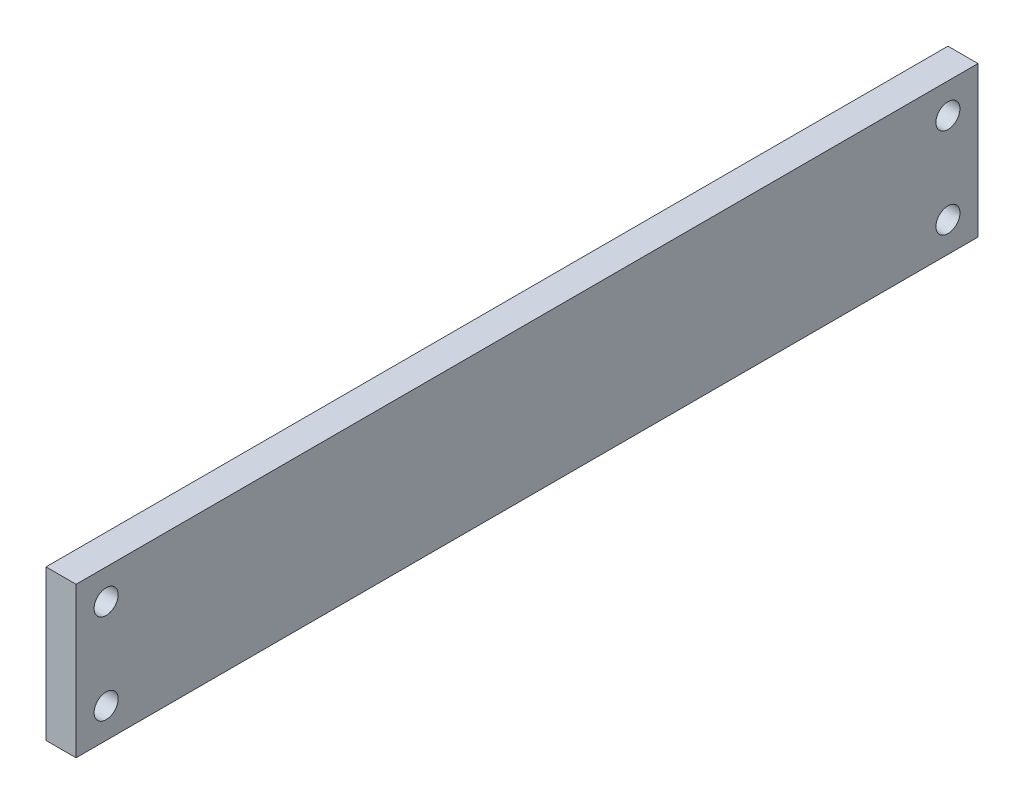
SolidWorks part; units mm, degrees
ref_plane "Front" through (0, 0, 0) normal (0, 0, 1) x (1, 0, 0)
ref_plane "Top" through (0, 0, 0) normal (0, 1, 0) x (1, 0, 0)
ref_plane "Right" through (0, 0, 0) normal (1, 0, 0) x (0, 0, -1)
sketch "Sketch1" plane through (0, 0, 0) normal (1, 0, 0) x (0, 0, -1)
  line L0 (-75, 12.5) -> (75, -12.5) construction
  line L1 (75, -12.5) -> (-75, -12.5)
  line L2 (75, -12.5) -> (75, 12.5)
  line L3 (75, 12.5) -> (-75, 12.5)
  line L4 (-75, -12.5) -> (-75, 12.5)
  dimension "D1" = 25
  dimension "D2" = 150
extrude "Boss-Extrude1" add sketch "Sketch1" along normal blind 5
sketch "Sketch2" plane through (5, 0, 0) normal (1, 0, 0) x (0, 0, -1)
  line L0 (0, -12.5) -> (0, 12.5) construction
  line L1 (-70, 7.5) -> (70, 7.5) construction
  line L2 (-70, 7.5) -> (-70, -7.5) construction
  line L3 (-70, -7.5) -> (70, -7.5) construction
  line L4 (70, 7.5) -> (70, -7.5) construction
  line L5 (-75, -12.5) -> (75, -12.5) construction
  line L6 (75, 12.5) -> (-75, 12.5) construction
  line L7 (-75, 0) -> (75, 0) construction
  line L8 (-75, 12.5) -> (-75, -12.5) construction
  line L9 (75, -12.5) -> (75, 12.5) construction
  circle A0 centre (-70, 7.5) radius 2
  circle A1 centre (-70, -7.5) radius 2
  circle A2 centre (70, -7.5) radius 2
  circle A3 centre (70, 7.5) radius 2
  point P20 (-57.3226, -7.5)
  dimension "D1" = 4
  dimension "D2" = 15
  dimension "D3" = 5
extrude "Cut-Extrude1" cut sketch "Sketch2" against normal blind 5
